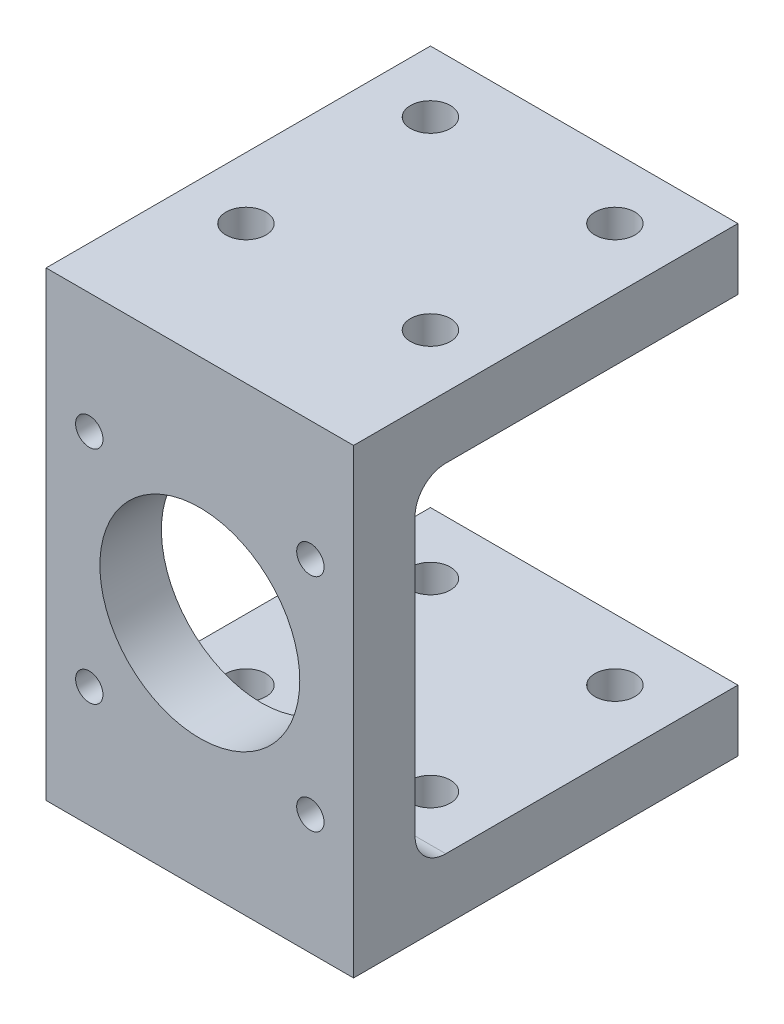
SolidWorks part; units mm, degrees
material "ABS"
ref_plane "Front Plane" through (0, 0, 0) normal (0, 0, 1) x (1, 0, 0)
ref_plane "Top Plane" through (0, 0, 0) normal (0, 1, 0) x (1, 0, 0)
ref_plane "Right Plane" through (0, 0, 0) normal (1, 0, 0) x (0, 0, -1)
sketch "Sketch1" plane through (0, 0, 0) normal (0, 0, 1) x (1, 0, 0)
  line L1 (-12.7, -19.05) -> (12.7, -19.05)
  line L2 (-12.7, -19.05) -> (-12.7, 19.05)
  line L3 (-12.7, 19.05) -> (12.7, 19.05)
  line L4 (12.7, -19.05) -> (12.7, 19.05)
  line L5 (-12.7, -19.05) -> (12.7, 19.05) construction
  line L6 (-12.7, 19.05) -> (12.7, -19.05) construction
  line L7 (-9.1313, -9.1313) -> (9.1313, -9.1313) construction
  line L8 (-9.1313, -9.1313) -> (-9.1313, 9.1313) construction
  line L9 (-9.1313, 9.1313) -> (9.1313, 9.1313) construction
  line L10 (9.1313, -9.1313) -> (9.1313, 9.1313) construction
  line L11 (-9.1313, -9.1313) -> (9.1313, 9.1313) construction
  line L12 (-9.1313, 9.1313) -> (9.1313, -9.1313) construction
  circle A0 centre (0, 0) radius 8.255
  circle A1 centre (-9.1313, 9.1313) radius 1.1303
  circle A2 centre (9.1313, 9.1313) radius 1.1303
  circle A3 centre (-9.1313, -9.1313) radius 1.1303
  circle A4 centre (9.1313, -9.1313) radius 1.1303
  point P0 (0, 0)
  dimension "D3" = 16.51
  dimension "D5" = 2.2606
  dimension "D1" = 38.1
  dimension "D2" = 25.4
  dimension "D4" = 18.2626
  dimension "D6" = 18.2626
extrude "Boss-Extrude with 4-40 Tap Drill Holes" add sketch "Sketch1" against normal mid plane 31.75
sketch "Sketch3" plane through (12.7, 0, 0) normal (1, 0, 0) x (0, 0, -1)
  line L0 (15.875, -19.05) -> (15.875, 19.05) construction
  line L1 (15.875, 13.97) -> (-10.795, 13.97)
  line L2 (15.875, 13.97) -> (15.875, -13.97)
  line L3 (15.875, -13.97) -> (-10.795, -13.97)
  line L4 (-10.795, 13.97) -> (-10.795, -13.97)
  line L5 (15.875, 19.05) -> (-15.875, 19.05) construction
  line L6 (15.875, -19.05) -> (-15.875, -19.05) construction
  line L7 (-15.875, -19.05) -> (-15.875, 19.05) construction
  dimension "D1" = 5.08
  dimension "D2" = 5.08
  dimension "D3" = 5.08
extrude "Cut-Extrude1" cut sketch "Sketch3" against normal up to next
fillet "Fillet1" radius 2.54 2 edges at (0, -13.97, 10.795) (0, 13.97, 10.795)
sketch "Sketch5" plane through (0, 19.05, 0) normal (0, 1, 0) x (1, 0, 0)
  line L4 (-12.7, 15.875) -> (-12.7, -8.255)
  line L5 (-12.7, 15.875) -> (-12.7, -8.255)
  line L6 (12.7, -8.255) -> (12.7, 15.875)
  line L7 (12.7, 15.875) -> (-12.7, 15.875)
  line L8 (-12.7, -8.255) -> (12.7, -8.255)
  line L9 (-12.7, -8.255) -> (12.7, -8.255)
  line L10 (12.7, -8.255) -> (12.7, 15.875)
  line L11 (12.7, 15.875) -> (-12.7, 15.875)
  circle A0 centre (-7.62, 10.795) radius 1.65
  circle A1 centre (7.62, 10.795) radius 1.65
  circle A2 centre (7.62, -4.445) radius 1.65
  circle A3 centre (-7.62, -4.445) radius 1.65
  dimension "D2" = 3.3
  dimension "D3" = 5.08
  dimension "D4" = 5.08
  dimension "D5" = 5.08
  dimension "D6" = 3.81
  dimension "D1" = 0
extrude "Clearance Holes for M3 Screw" cut sketch "Sketch5" against normal through all contours A0 | A3 | A2 | A1
